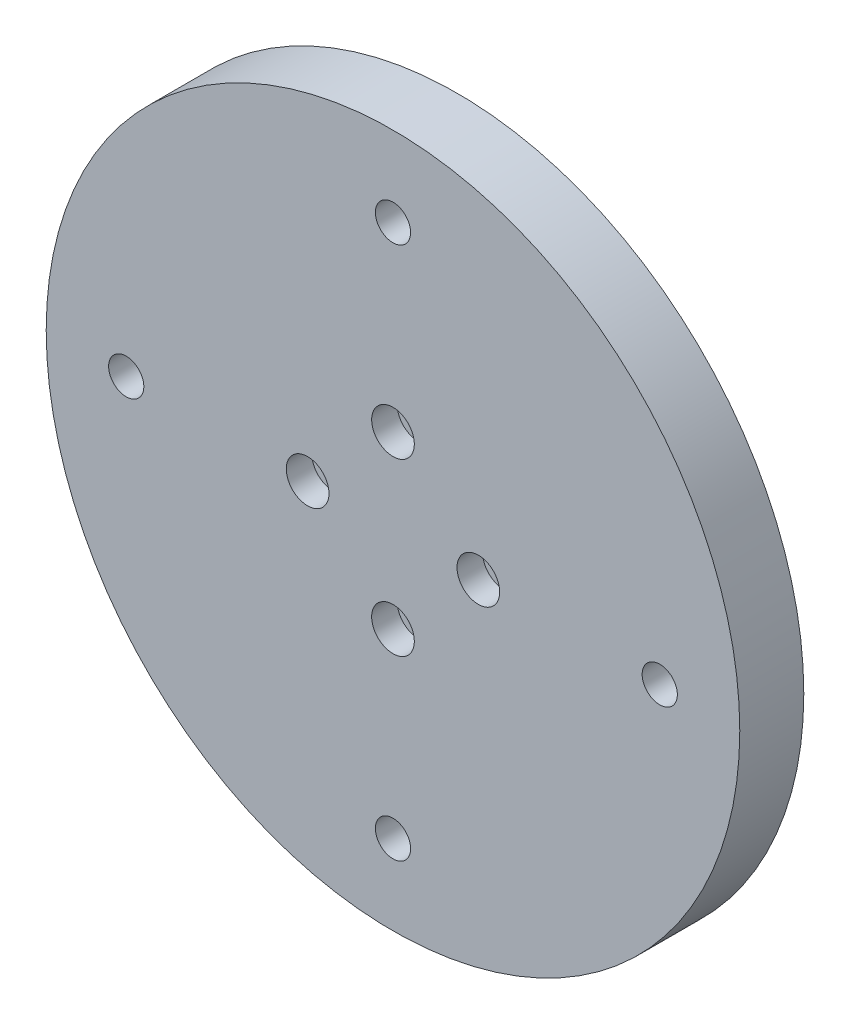
SolidWorks part; units mm, degrees
ref_plane "Front Plane" through (0, 0, 0) normal (0, 0, 1) x (1, 0, 0)
ref_plane "Top Plane" through (0, 0, 0) normal (0, 1, 0) x (1, 0, 0)
ref_plane "Right Plane" through (0, 0, 0) normal (1, 0, 0) x (0, 0, -1)
sketch "Sketch1" plane through (0, 0, 0) normal (0, 0, 1) x (1, 0, 0)
  circle A0 centre (0, 0) radius 32.5
  dimension "D1" = 65
extrude "Boss-Extrude1" add sketch "Sketch1" along normal blind 6
sketch "Sketch16" plane through (0, 0, 6) normal (0, 0, 1) x (1, 0, 0)
  line L0 (-8, 0) -> (8, 0) construction
  line L1 (0, 0) -> (0, -8) construction
  line L2 (0, 0) -> (0, 8) construction
  circle A0 centre (8, 0) radius 1.1
  circle A1 centre (-8, 0) radius 1.1
  circle A2 centre (0, -8) radius 1.1
  circle A3 centre (0, 8) radius 1.1
  point P6 (0, 0)
  dimension "D1" = 2.2
  dimension "D2" = 8
  dimension "D3" = 16
  dimension "D4" = 8
extrude "Cut-Extrude8" cut sketch "Sketch16" against normal through all
sketch "Sketch17" plane through (0, 0, 6) normal (0, 0, 1) x (1, 0, 0)
  circle A0 centre (8, 0) radius 2
  circle A1 centre (-8, 0) radius 2
  circle A2 centre (0, -8) radius 2
  circle A3 centre (0, 8) radius 2
  dimension "D1" = 4
extrude "Cut-Extrude9" cut sketch "Sketch17" against normal blind 2.4
sketch "Sketch12" plane through (0, 0, 6) normal (0, 0, 1) x (1, 0, 0)
  line L0 (0, 0) -> (0, 25) construction
  circle A4 centre (0, 25) radius 1.65
  circle A5 centre (25, 0) radius 1.65
  circle A6 centre (0, -25) radius 1.65
  circle A7 centre (-25, 0) radius 1.65
  point P14 (0, 0)
  dimension "D3" = 4
  dimension "D1" = 3.3
  dimension "D2" = 25
extrude "Cut-Extrude10" cut sketch "Sketch12" against normal through all
